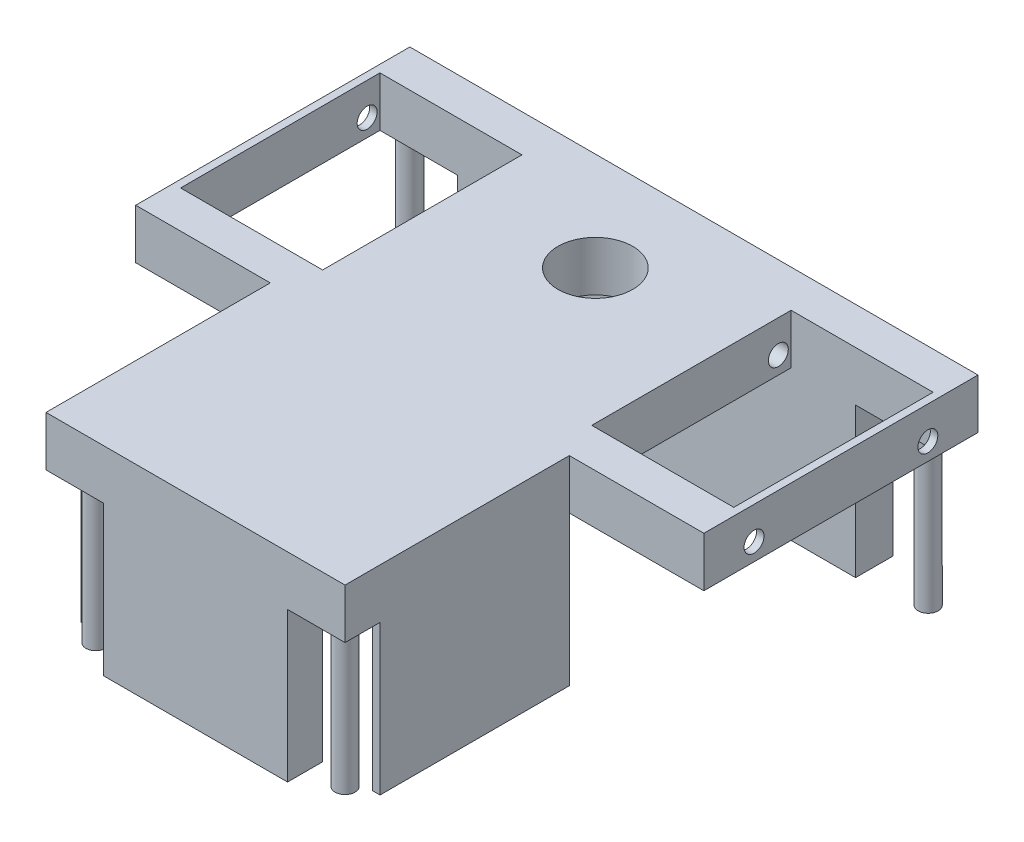
SolidWorks part; units mm, degrees
ref_plane "Front Plane" through (0, 0, 0) normal (0, 0, 1) x (1, 0, 0)
ref_plane "Top Plane" through (0, 0, 0) normal (0, 1, 0) x (1, 0, 0)
ref_plane "Right Plane" through (0, 0, 0) normal (1, 0, 0) x (0, 0, -1)
sketch "Sketch1" plane through (0, 0, 0) normal (0, 1, 0) x (1, 0, 0)
  line L0 (0, 0) -> (0, 226.5914) construction
  line L1 (30, 0) -> (-30, 0)
  line L2 (-30, 0) -> (-30, 45)
  line L3 (-30, 45) -> (-57, 45)
  line L4 (-57, 45) -> (-57, 100)
  line L5 (-57, 100) -> (57, 100)
  line L6 (30, 0) -> (30, 45)
  line L7 (30, 45) -> (57, 45)
  line L8 (57, 45) -> (57, 100)
  point P11 (0, 0)
  point P14 (0, 100)
  dimension "D1" = 30
  dimension "D2" = 45
  dimension "D3" = 55
extrude "Boss-Extrude1" add sketch "Sketch1" along normal blind 10 contours L3 L4 L5 L8 L7 L6 L1 L2
sketch "Sketch2" plane through (0, 10, 0) normal (0, 1, 0) x (1, 0, 0)
  line L0 (-57, 72.5) -> (57, 72.5) construction
  line L1 (-57, 45) -> (-57, 100) construction
  line L2 (57, 45) -> (57, 100) construction
  line L3 (-55.5, 52.5) -> (-55.5, 92.5)
  line L4 (-55.5, 92.5) -> (-27, 92.5)
  line L5 (-27, 92.5) -> (-27, 52.5)
  line L6 (-55.5, 52.5) -> (-27, 52.5)
  line L7 (0, 100) -> (0, 0) construction
  line L8 (-57, 100) -> (57, 100) construction
  line L9 (27, 92.5) -> (27, 52.5)
  line L10 (55.5, 52.5) -> (27, 52.5)
  line L11 (55.5, 52.5) -> (55.5, 92.5)
  line L12 (55.5, 92.5) -> (27, 92.5)
  line L13 (-30, 0) -> (-30, 45) construction
  line L15 (30, 0) -> (-30, 0) construction
  circle A0 centre (-52, 95) radius 2
  circle A1 centre (52, 95) radius 2
  circle A2 centre (-25, 5) radius 2
  circle A3 centre (25, 5) radius 2
  circle A4 centre (25, 5) radius 2
  circle A5 centre (-25, 5) radius 2
  circle A6 centre (52, 95) radius 2
  circle A7 centre (-52, 95) radius 2
  point P11 (-27, 72.5)
  point P12 (-55.5, 72.5)
  dimension "D4" = 4
  dimension "D7" = 4
  dimension "D1" = 1.5
  dimension "D2" = 28.5
  dimension "D3" = 40
  dimension "D5" = 5
  dimension "D6" = 5
  dimension "D8" = 5
  dimension "D9" = 5
extrude "Cut-Extrude1" cut sketch "Sketch2" against normal through all both and the other way through all contours A1 | A2 | A3 | L5 L6 L3 L4 | L9 L10 L11 L12 | A0
sketch "Sketch5" plane through (57, 0, 0) normal (1, 0, 0) x (0, 0, -1)
  line L0 (72.5, 10) -> (72.5, 0) construction
  line L1 (45, 10) -> (100, 10) construction
  line L2 (45, 0) -> (100, 0) construction
  circle A0 centre (55.0644, 3.5) radius 2
  circle A1 centre (89.9356, 3.5) radius 2
  point P14 (72.5, 5)
  dimension "D1" = 17.5
  dimension "D2" = 3.5
extrude "Cut-Extrude2" cut sketch "Sketch5" against normal through all
sketch "Sketch6" plane through (0, 10, 0) normal (0, 1, 0) x (1, 0, 0)
  circle A0 centre (-25, 5) radius 2
  circle A1 centre (25, 5) radius 2
  circle A2 centre (52, 95) radius 2
  circle A3 centre (-52, 95) radius 2
extrude "Boss-Extrude2" add sketch "Sketch6" against normal blind 40
sketch "Sketch7" plane through (0, 0, 0) normal (0, -1, 0) x (1, 0, 0)
  line L0 (-55.5, -92.5) -> (-27, -92.5) construction
  line L1 (-39.9371, -92.5) -> (39.9371, -92.5)
  line L2 (-39.9371, -92.5) -> (-39.9371, -100)
  line L3 (-39.9371, -100) -> (39.9371, -100)
  line L4 (39.9371, -92.5) -> (39.9371, -100)
  line L5 (-57, -100) -> (57, -100) construction
  line L6 (30, 0) -> (-30, 0) construction
  line L7 (-18.467, 0) -> (18.467, 0)
  line L8 (-18.467, 0) -> (-18.467, -7.0219)
  line L9 (-18.467, -7.0219) -> (18.467, -7.0219)
  line L10 (18.467, 0) -> (18.467, -7.0219)
  line L11 (-25, -5) -> (-18.467, -5) construction
  line L12 (25, -5) -> (18.467, -5) construction
  line L13 (-52, -95) -> (-39.9371, -95) construction
  line L14 (52, -95) -> (39.9371, -95) construction
  line L15 (-30, 0) -> (-30, -45) construction
  line L16 (-30, -7.0219) -> (-28.5, -7.0219)
  line L17 (-30, -7.0219) -> (-30, -45)
  line L18 (-30, -45) -> (-28.5, -45)
  line L19 (-28.5, -7.0219) -> (-28.5, -45)
  line L20 (0, 0) -> (0, -100) construction
  line L21 (30, -45) -> (28.5, -45)
  line L22 (30, -7.0219) -> (28.5, -7.0219)
  line L23 (30, -7.0219) -> (30, -45)
  line L24 (28.5, -7.0219) -> (28.5, -45)
  dimension "D1" = 1.5
extrude "Boss-Extrude3" add sketch "Sketch7" along normal blind 30
sketch "Sketch8" plane through (0, 10, 0) normal (0, 1, 0) x (1, 0, 0)
  line L0 (0, 100) -> (0, 0) construction
  line L1 (-57, 100) -> (57, 100) construction
  line L2 (30, 0) -> (-30, 0) construction
  circle A0 centre (0, 80.2271) radius 7.5
  dimension "D1" = 15
extrude "Cut-Extrude3" cut sketch "Sketch8" against normal through all both and the other way through all
